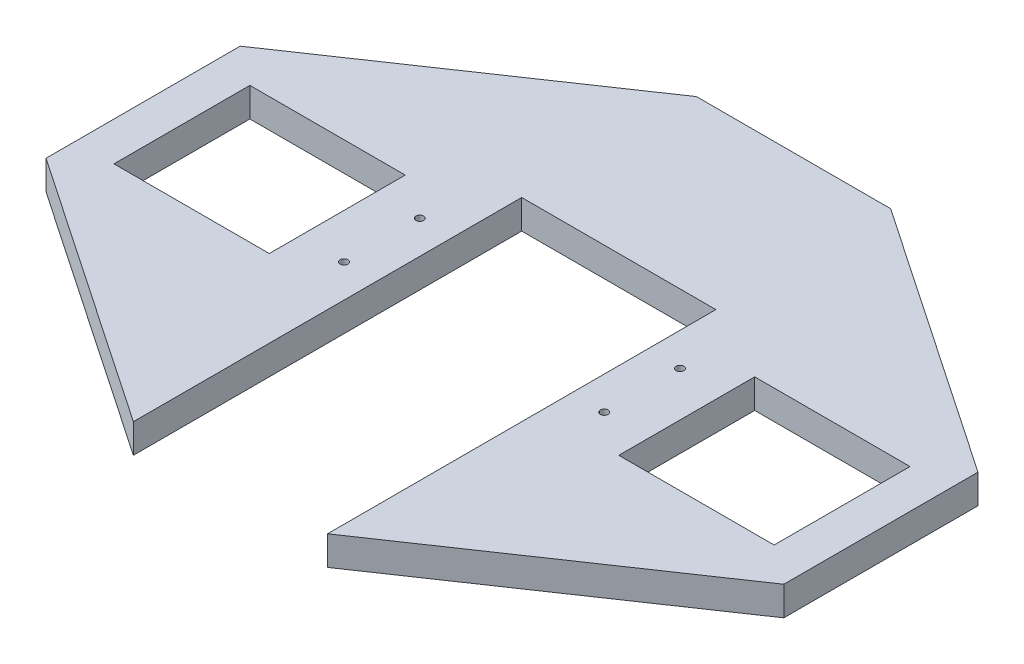
SolidWorks part; units mm, degrees
material "Balsa"
ref_plane "Plan de face" through (0, 0, 0) normal (0, 0, 1) x (1, 0, 0)
ref_plane "Plan de dessus" through (0, 0, 0) normal (0, 1, 0) x (1, 0, 0)
ref_plane "Plan de droite" through (0, 0, 0) normal (1, 0, 0) x (0, 0, -1)
sketch "Esquisse1" plane through (0, 0, 0) normal (0, 1, 0) x (1, 0, 0)
  line L0 (-76.6432, -51.4013) -> (63.3568, 43.5987)
  line L1 (63.3568, 43.5987) -> (163.3568, 43.5987)
  line L2 (-76.6432, -51.4013) -> (-76.6432, -151.4013)
  line L3 (63.3568, -246.4013) -> (163.3568, -246.4013)
  line L4 (303.3568, -51.4013) -> (303.3568, -151.4013)
  line L5 (163.3568, 43.5987) -> (303.3568, -51.4013)
  line L6 (163.3568, -246.4013) -> (303.3568, -151.4013)
  line L7 (-76.6432, -151.4013) -> (63.3568, -246.4013)
  point P0 (-76.6432, 43.5987)
  point P1 (303.3568, -246.4013)
  point P2 (-76.6432, -246.4013)
  point P3 (303.3568, 43.5987)
  dimension "D1" = 380
  dimension "D2" = 290
  dimension "D3" = 140
  dimension "D4" = 95
  dimension "D5" = 140
  dimension "D6" = 95
  dimension "D7" = 140
  dimension "D8" = 95
  dimension "D9" = 95
  dimension "D10" = 140
extrude "Boss.-Extru.1" add sketch "Esquisse1" along normal blind 15 contours L0 L1 L5 L4 L6 L3 L7 L2
sketch "Esquisse6" plane through (0, 0, 246.4013) normal (0, 0, 1) x (1, 0, 0)
  line L1 (63.3568, 15) -> (163.3568, 15)
  line L2 (63.3568, 15) -> (63.3568, 0)
  line L3 (63.3568, 0) -> (163.3568, 0)
  line L4 (163.3568, 15) -> (163.3568, 0)
extrude "Enlèv. mat.-Extru.1" cut sketch "Esquisse6" against normal blind 200
sketch "Esquisse7" plane through (0, 15, 0) normal (0, 1, 0) x (1, 0, 0)
  line L0 (-76.6432, -51.4013) -> (-76.6432, -151.4013) construction
  line L1 (23.3568, -136.4013) -> (-56.6432, -136.4013)
  line L2 (23.3568, -136.4013) -> (23.3568, -66.4013)
  line L3 (23.3568, -66.4013) -> (-56.6432, -66.4013)
  line L4 (-56.6432, -136.4013) -> (-56.6432, -66.4013)
  line L5 (163.3568, -46.4013) -> (63.3568, -46.4013) construction
  line L6 (303.3568, -51.4013) -> (303.3568, -151.4013) construction
  line L7 (283.3568, -136.4013) -> (203.3568, -136.4013)
  line L8 (283.3568, -136.4013) -> (283.3568, -66.4013)
  line L9 (283.3568, -66.4013) -> (203.3568, -66.4013)
  line L10 (203.3568, -136.4013) -> (203.3568, -66.4013)
  dimension "D1" = 70
  dimension "D2" = 20
  dimension "D3" = 80
  dimension "D4" = 20
  dimension "D5" = 70
  dimension "D6" = 80
  dimension "D7" = 20
  dimension "D8" = 20
extrude "Enlèv. mat.-Extru.2" cut sketch "Esquisse7" against normal up to next
sketch "Esquisse8" plane through (0, 15, 0) normal (0, 1, 0) x (1, 0, 0)
  line L0 (203.3568, -66.4013) -> (203.3568, -136.4013) construction
  line L1 (203.3568, -136.4013) -> (283.3568, -136.4013) construction
  line L2 (23.3568, -136.4013) -> (23.3568, -66.4013) construction
  line L3 (-56.6432, -136.4013) -> (23.3568, -136.4013) construction
  circle A0 centre (180.3568, -120.9013) radius 2
  circle A1 centre (180.3568, -81.9013) radius 2
  circle A2 centre (46.3568, -120.9013) radius 2
  circle A3 centre (46.3568, -81.9013) radius 2
  dimension "D1" = 4
  dimension "D3" = 4
  dimension "D11" = 4
  dimension "D12" = 4
  dimension "D2" = 23
  dimension "D4" = 23
  dimension "D5" = 39
  dimension "D6" = 15.5
  dimension "D7" = 23
  dimension "D8" = 23
  dimension "D9" = 39
  dimension "D10" = 15.5
extrude "Enlèv. mat.-Extru.4" cut sketch "Esquisse8" against normal up to next contours A0 | A2 | A1 | A3
